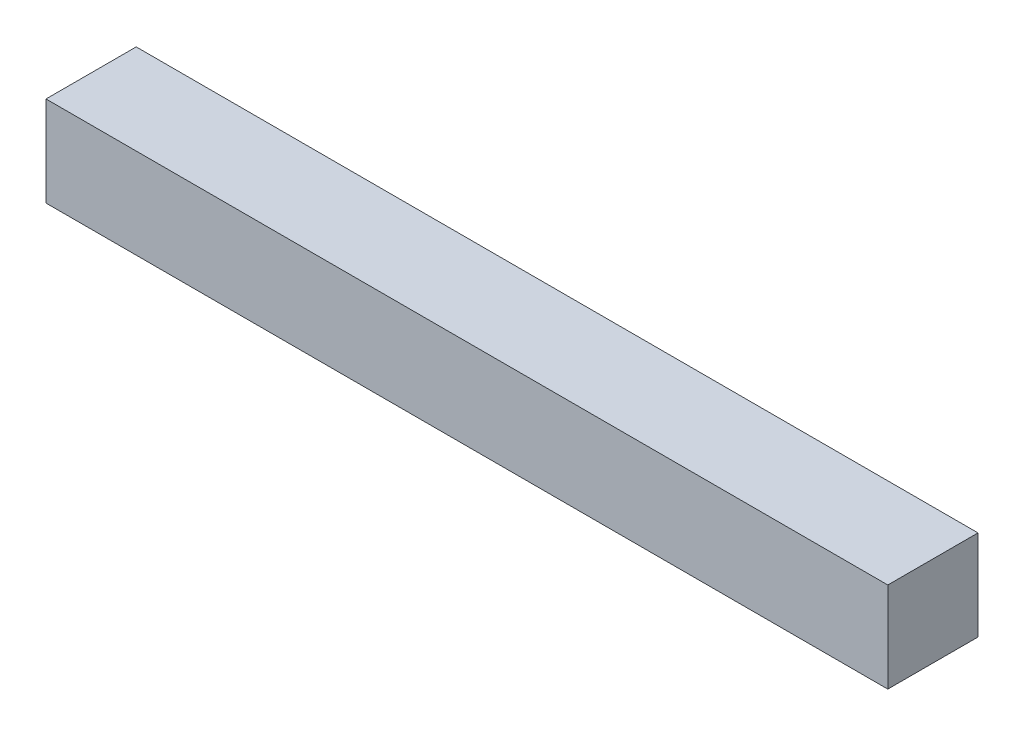
SolidWorks part; units mm, degrees
material "Pine"
ref_plane "X-Y Datum" through (0, 0, 0) normal (0, 0, 1) x (1, 0, 0)
ref_plane "X-Z Datum" through (0, 0, 0) normal (0, 1, 0) x (1, 0, 0)
ref_plane "Y-Z Datum" through (0, 0, 0) normal (1, 0, 0) x (0, 0, -1)
sketch "Sketch1" plane through (0, 0, 0) normal (1, 0, 0) x (0, 0, -1)
  line L1 (-19.05, 19.05) -> (19.05, 19.05)
  line L2 (-19.05, 19.05) -> (-19.05, -19.05)
  line L3 (-19.05, -19.05) -> (19.05, -19.05)
  line L4 (19.05, 19.05) -> (19.05, -19.05)
  line L5 (-19.05, 19.05) -> (19.05, -19.05) construction
  line L6 (-19.05, -19.05) -> (19.05, 19.05) construction
  point P0 (0, 0)
  dimension "D1" = 38.1
extrude "Boss-Extrude1" add sketch "Sketch1" along normal blind 355.6
